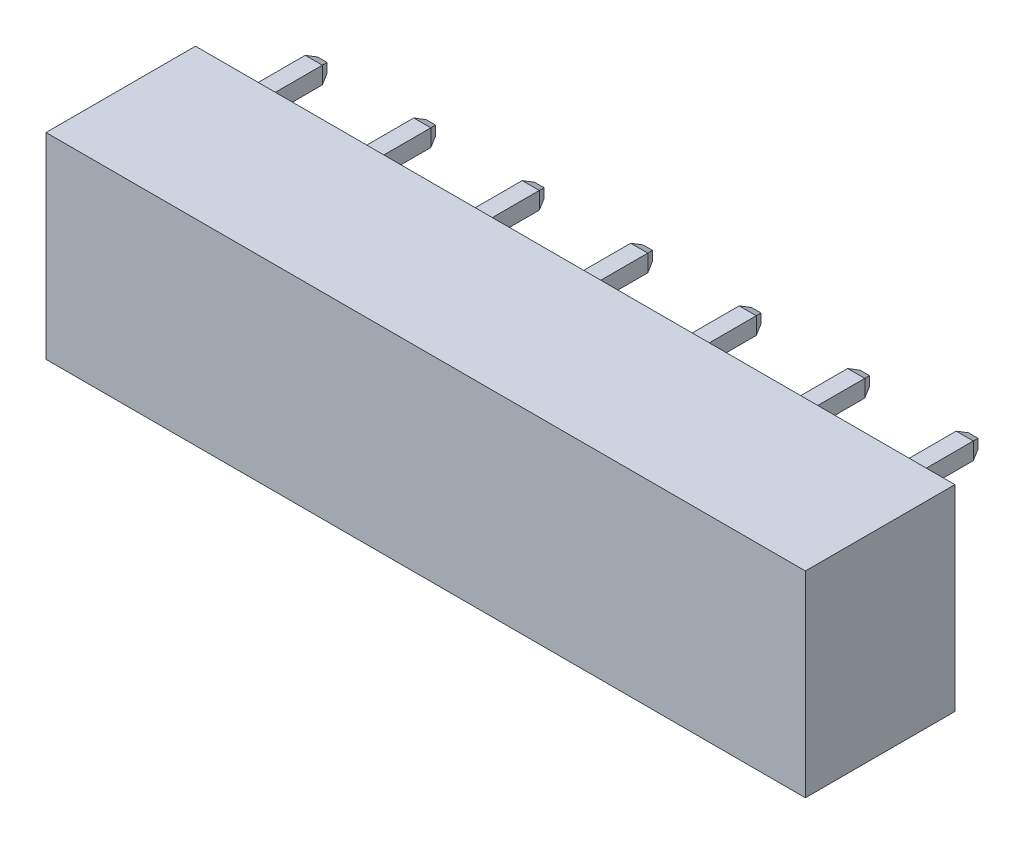
SolidWorks part; units mm, degrees
ref_plane "Спереди" through (0, 0, 0) normal (0, 0, 1) x (1, 0, 0)
ref_plane "Сверху" through (0, 0, 0) normal (0, 1, 0) x (1, 0, 0)
ref_plane "Справа" through (0, 0, 0) normal (1, 0, 0) x (0, 0, -1)
sketch "Эскиз1" plane through (0, 0, 0) normal (0, 0, 1) x (1, 0, 0)
  line L1 (17.78, 9.2) -> (-17.78, 9.2)
  line L2 (17.78, 9.2) -> (17.78, 0)
  line L3 (17.78, 0) -> (-17.78, 0)
  line L4 (-17.78, 9.2) -> (-17.78, 0)
  line L5 (17.78, 9.2) -> (-17.78, 0) construction
  line L6 (17.78, 0) -> (-17.78, 9.2) construction
  point P0 (0, 4.6)
  dimension "D1" = 9.2
  dimension "D2" = 35.56
extrude "Бобышка-Вытянуть1" add sketch "Эскиз1" along normal blind 7
sketch "Эскиз2" plane through (0, 0, 0) normal (0, 0, -1) x (-1, 0, 0)
  line L0 (17.78, 0) -> (-17.78, 0) construction
  line L1 (-15.64, 7.6) -> (-14.84, 7.6)
  line L2 (-15.64, 7.6) -> (-15.64, 8.4)
  line L3 (-15.64, 8.4) -> (-14.84, 8.4)
  line L4 (-14.84, 7.6) -> (-14.84, 8.4)
  line L5 (-15.64, 7.6) -> (-14.84, 8.4) construction
  line L6 (-15.64, 8.4) -> (-14.84, 7.6) construction
  line L7 (-17.78, 0) -> (-17.78, 9.2) construction
  point P0 (-15.24, 8)
  dimension "D1" = 8
  dimension "D2" = 0.8
  dimension "D3" = 2.54
extrude "Бобышка-Вытянуть2" add sketch "Эскиз2" along normal blind 3.4
chamfer "Фаска1" distance 0.4 angle 24 4 edges at (15.24, 8.4, -3.4) (14.84, 8, -3.4) (15.24, 7.6, -3.4) (15.64, 8, -3.4)
sketch "Эскиз3" plane through (0, 0, 0) normal (0, -1, 0) x (1, 0, 0)
  line L1 (13.74, 0.8) -> (16.74, 0.8)
  line L2 (13.74, 0.8) -> (13.74, 5)
  line L4 (16.74, 0.8) -> (16.74, 5)
  line L5 (13.74, 0.8) -> (16.74, 5) construction
  line L6 (13.74, 5) -> (16.74, 0.8) construction
  line L7 (-17.78, 0) -> (17.78, 0) construction
  line L9 (17.78, 7) -> (17.78, 0) construction
  line L10 (-17.78, 7) -> (17.78, 7) construction
  line L11 (13.74, 6.5) -> (16.74, 6.5)
  line L12 (13.74, 5) -> (14.74, 5)
  line L13 (14.74, 5) -> (13.74, 6.5)
  line L14 (16.74, 5) -> (15.74, 5)
  line L15 (15.74, 5) -> (16.74, 6.5)
  point P0 (15.24, 2.9)
  point P5 (15.24, 6.5)
  dimension "D1" = 2.54
  dimension "D2" = 0.8
  dimension "D3" = 2
  dimension "D4" = 3
  dimension "D5" = 0.5
  dimension "D6" = 1
extrude "Вырез-Вытянуть1" cut sketch "Эскиз3" against normal blind 7
pattern_linear "Линейный массив1" count 7 spacing 5.08 along (-1, 0, 0) of "Бобышка-Вытянуть2", "Фаска1"
pattern_linear "Линейный массив2" count 7 spacing 5.08 along (-1, 0, 0) of "Вырез-Вытянуть1"
sketch "Эскиз4" plane through (0, 7, 0) normal (0, -1, 0) x (1, 0, 0)
  line L0 (15.64, -3) -> (15.64, 0) construction
  line L1 (14.84, 3.4) -> (15.64, 3.4)
  line L2 (14.84, 3.4) -> (14.84, 2.6)
  line L3 (14.84, 2.6) -> (15.64, 2.6)
  line L4 (15.64, 3.4) -> (15.64, 2.6)
  line L5 (14.84, 3.4) -> (15.64, 2.6) construction
  line L6 (14.84, 2.6) -> (15.64, 3.4) construction
  line L7 (14.84, -3) -> (14.84, 0) construction
  line L8 (-17.78, 0) -> (17.78, 0) construction
  point P0 (15.24, 3)
  dimension "D1" = 3
extrude "Бобышка-Вытянуть3" add sketch "Эскиз4" along normal blind 6
chamfer "Фаска2" distance 0.4 angle 24 4 edges at (15.64, 1, 3) (15.24, 1, 3.4) (14.84, 1, 3) (15.24, 1, 2.6)
pattern_linear "Линейный массив3" count 7 spacing 5.08 along (-1, 0, 0) of "Фаска2", "Бобышка-Вытянуть3"
equation "\"n\"= 7"
equation "\"width\"= 3.5 * ( \"n\" - 1 ) + 4.3"
equation "\"D2@Эскиз1\"=5.08 * \"n\""
equation "\"D1@Линейный массив1\"=\"n\""
equation "\"D1@Линейный массив2\"=\"n\""
equation "\"D1@Линейный массив3\"=\"n\""
